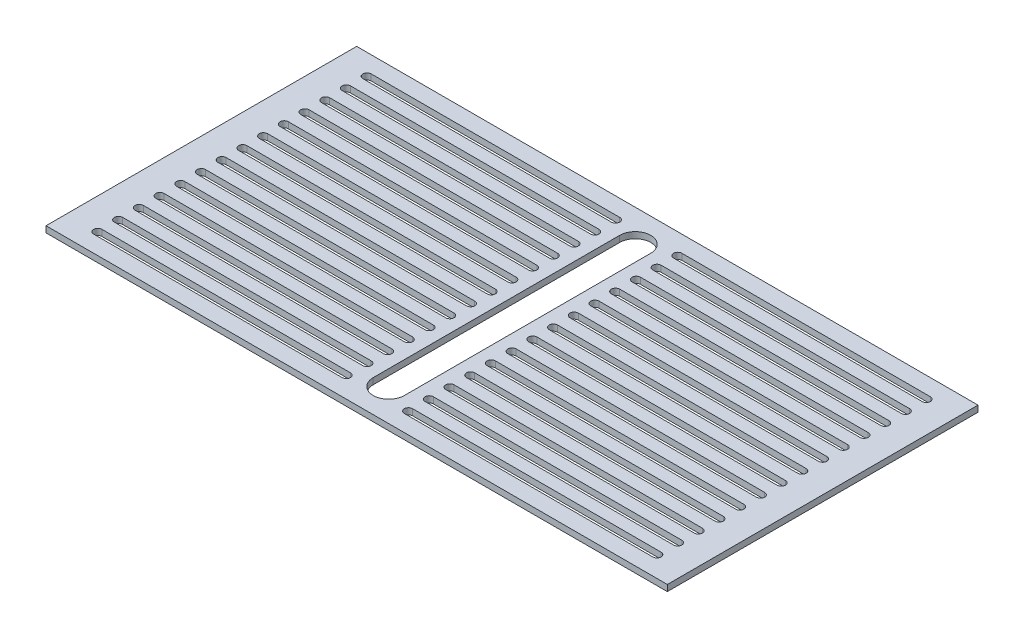
SolidWorks part; units mm, degrees
ref_plane "Front Plane" through (0, 0, 0) normal (0, 0, 1) x (1, 0, 0)
ref_plane "Top Plane" through (0, 0, 0) normal (0, 1, 0) x (1, 0, 0)
ref_plane "Right Plane" through (0, 0, 0) normal (1, 0, 0) x (0, 0, -1)
sketch "Sketch1" plane through (0, 0, 0) normal (0, 1, 0) x (1, 0, 0)
  line L1 (-150, 75) -> (150, 75)
  line L2 (-150, 75) -> (-150, -75)
  line L3 (-150, -75) -> (150, -75)
  line L4 (150, 75) -> (150, -75)
  line L5 (-150, 75) -> (150, -75) construction
  line L6 (-150, -75) -> (150, 75) construction
  point P0 (0, 0)
  dimension "D1" = 300
  dimension "D2" = 150
extrude "Boss-Extrude1" add sketch "Sketch1" along normal blind 3
sketch "Sketch2" plane through (0, 3, 0) normal (0, 1, 0) x (1, 0, 0)
  line L0 (0, 75) -> (0, -75) construction
  line L1 (150, 75) -> (-150, 75) construction
  line L2 (-150, -75) -> (150, -75) construction
  line L3 (-150, 0) -> (150, 0) construction
  line L4 (-150, 75) -> (-150, -75) construction
  line L5 (150, -75) -> (150, 75) construction
  line L6 (-150, 65) -> (0, 65) construction
  line L7 (-135, 65) -> (-15, 65) construction
  line L8 (-135, 67) -> (-15, 67)
  line L9 (-135, 63) -> (-15, 63)
  line L10 (15, 65) -> (135, 65) construction
  line L11 (15, 67) -> (135, 67)
  line L12 (15, 63) -> (135, 63)
  line L13 (15, 55) -> (135, 55) construction
  line L14 (15, 57) -> (135, 57)
  line L15 (15, 53) -> (135, 53)
  line L16 (15, 45) -> (135, 45) construction
  line L17 (15, 47) -> (135, 47)
  line L18 (15, 43) -> (135, 43)
  line L19 (15, 35) -> (135, 35) construction
  line L20 (15, 37) -> (135, 37)
  line L21 (15, 33) -> (135, 33)
  line L22 (15, 25) -> (135, 25) construction
  line L23 (15, 27) -> (135, 27)
  line L24 (15, 23) -> (135, 23)
  line L25 (15, 15) -> (135, 15) construction
  line L26 (15, 17) -> (135, 17)
  line L27 (15, 13) -> (135, 13)
  line L28 (15, 5) -> (135, 5) construction
  line L29 (15, 7) -> (135, 7)
  line L30 (15, 3) -> (135, 3)
  line L31 (15, -5) -> (135, -5) construction
  line L32 (15, -3) -> (135, -3)
  line L33 (15, -7) -> (135, -7)
  line L34 (15, -15) -> (135, -15) construction
  line L35 (15, -13) -> (135, -13)
  line L36 (15, -17) -> (135, -17)
  line L37 (15, -25) -> (135, -25) construction
  line L38 (15, -23) -> (135, -23)
  line L39 (15, -27) -> (135, -27)
  line L40 (15, -35) -> (135, -35) construction
  line L41 (15, -33) -> (135, -33)
  line L42 (15, -37) -> (135, -37)
  line L43 (15, -45) -> (135, -45) construction
  line L44 (15, -43) -> (135, -43)
  line L45 (15, -47) -> (135, -47)
  line L46 (15, -55) -> (135, -55) construction
  line L47 (15, -53) -> (135, -53)
  line L48 (15, -57) -> (135, -57)
  line L49 (15, -65) -> (135, -65) construction
  line L50 (15, -63) -> (135, -63)
  line L51 (15, -67) -> (135, -67)
  line L52 (-135, 55) -> (-15, 55) construction
  line L53 (-135, 57) -> (-15, 57)
  line L54 (-135, 53) -> (-15, 53)
  line L55 (-135, 45) -> (-15, 45) construction
  line L56 (-135, 47) -> (-15, 47)
  line L57 (-135, 43) -> (-15, 43)
  line L58 (-135, 35) -> (-15, 35) construction
  line L59 (-135, 37) -> (-15, 37)
  line L60 (-135, 33) -> (-15, 33)
  line L61 (-135, 25) -> (-15, 25) construction
  line L62 (-135, 27) -> (-15, 27)
  line L63 (-135, 23) -> (-15, 23)
  line L64 (-135, 15) -> (-15, 15) construction
  line L65 (-135, 17) -> (-15, 17)
  line L66 (-135, 13) -> (-15, 13)
  line L67 (-135, 5) -> (-15, 5) construction
  line L68 (-135, 7) -> (-15, 7)
  line L69 (-135, 3) -> (-15, 3)
  line L70 (-135, -5) -> (-15, -5) construction
  line L71 (-135, -3) -> (-15, -3)
  line L72 (-135, -7) -> (-15, -7)
  line L73 (-135, -15) -> (-15, -15) construction
  line L74 (-135, -13) -> (-15, -13)
  line L75 (-135, -17) -> (-15, -17)
  line L76 (-135, -25) -> (-15, -25) construction
  line L77 (-135, -23) -> (-15, -23)
  line L78 (-135, -27) -> (-15, -27)
  line L79 (-135, -35) -> (-15, -35) construction
  line L80 (-135, -33) -> (-15, -33)
  line L81 (-135, -37) -> (-15, -37)
  line L82 (-135, -45) -> (-15, -45) construction
  line L83 (-135, -43) -> (-15, -43)
  line L84 (-135, -47) -> (-15, -47)
  line L85 (-135, -55) -> (-15, -55) construction
  line L86 (-135, -53) -> (-15, -53)
  line L87 (-135, -57) -> (-15, -57)
  line L88 (-135, -65) -> (-15, -65) construction
  line L89 (-135, -63) -> (-15, -63)
  line L90 (-135, -67) -> (-15, -67)
  line L91 (-75, 65) -> (-75, 55) construction
  line L92 (-135, 65) -> (-135, 75) construction
  line L93 (0, -59.5) -> (0, 59.5) construction
  line L94 (-7.5, -59.5) -> (-7.5, 59.5)
  line L95 (7.5, -59.5) -> (7.5, 59.5)
  line L96 (0, 67) -> (-15, 67) construction
  arc A0 (-135, 67) -> (-135, 63) centre (-135, 65) ccw
  arc A1 (-15, 63) -> (-15, 67) centre (-15, 65) ccw
  arc A2 (15, 67) -> (15, 63) centre (15, 65) ccw
  arc A3 (135, 63) -> (135, 67) centre (135, 65) ccw
  arc A4 (15, 57) -> (15, 53) centre (15, 55) ccw
  arc A5 (135, 53) -> (135, 57) centre (135, 55) ccw
  arc A6 (15, 47) -> (15, 43) centre (15, 45) ccw
  arc A7 (135, 43) -> (135, 47) centre (135, 45) ccw
  arc A8 (15, 37) -> (15, 33) centre (15, 35) ccw
  arc A9 (135, 33) -> (135, 37) centre (135, 35) ccw
  arc A10 (15, 27) -> (15, 23) centre (15, 25) ccw
  arc A11 (135, 23) -> (135, 27) centre (135, 25) ccw
  arc A12 (15, 17) -> (15, 13) centre (15, 15) ccw
  arc A13 (135, 13) -> (135, 17) centre (135, 15) ccw
  arc A14 (15, 7) -> (15, 3) centre (15, 5) ccw
  arc A15 (135, 3) -> (135, 7) centre (135, 5) ccw
  arc A16 (15, -3) -> (15, -7) centre (15, -5) ccw
  arc A17 (135, -7) -> (135, -3) centre (135, -5) ccw
  arc A18 (15, -13) -> (15, -17) centre (15, -15) ccw
  arc A19 (135, -17) -> (135, -13) centre (135, -15) ccw
  arc A20 (15, -23) -> (15, -27) centre (15, -25) ccw
  arc A21 (135, -27) -> (135, -23) centre (135, -25) ccw
  arc A22 (15, -33) -> (15, -37) centre (15, -35) ccw
  arc A23 (135, -37) -> (135, -33) centre (135, -35) ccw
  arc A24 (15, -43) -> (15, -47) centre (15, -45) ccw
  arc A25 (135, -47) -> (135, -43) centre (135, -45) ccw
  arc A26 (15, -53) -> (15, -57) centre (15, -55) ccw
  arc A27 (135, -57) -> (135, -53) centre (135, -55) ccw
  arc A28 (15, -63) -> (15, -67) centre (15, -65) ccw
  arc A29 (135, -67) -> (135, -63) centre (135, -65) ccw
  arc A30 (-135, 57) -> (-135, 53) centre (-135, 55) ccw
  arc A31 (-15, 53) -> (-15, 57) centre (-15, 55) ccw
  arc A32 (-135, 47) -> (-135, 43) centre (-135, 45) ccw
  arc A33 (-15, 43) -> (-15, 47) centre (-15, 45) ccw
  arc A34 (-135, 37) -> (-135, 33) centre (-135, 35) ccw
  arc A35 (-15, 33) -> (-15, 37) centre (-15, 35) ccw
  arc A36 (-135, 27) -> (-135, 23) centre (-135, 25) ccw
  arc A37 (-15, 23) -> (-15, 27) centre (-15, 25) ccw
  arc A38 (-135, 17) -> (-135, 13) centre (-135, 15) ccw
  arc A39 (-15, 13) -> (-15, 17) centre (-15, 15) ccw
  arc A40 (-135, 7) -> (-135, 3) centre (-135, 5) ccw
  arc A41 (-15, 3) -> (-15, 7) centre (-15, 5) ccw
  arc A42 (-135, -3) -> (-135, -7) centre (-135, -5) ccw
  arc A43 (-15, -7) -> (-15, -3) centre (-15, -5) ccw
  arc A44 (-135, -13) -> (-135, -17) centre (-135, -15) ccw
  arc A45 (-15, -17) -> (-15, -13) centre (-15, -15) ccw
  arc A46 (-135, -23) -> (-135, -27) centre (-135, -25) ccw
  arc A47 (-15, -27) -> (-15, -23) centre (-15, -25) ccw
  arc A48 (-135, -33) -> (-135, -37) centre (-135, -35) ccw
  arc A49 (-15, -37) -> (-15, -33) centre (-15, -35) ccw
  arc A50 (-135, -43) -> (-135, -47) centre (-135, -45) ccw
  arc A51 (-15, -47) -> (-15, -43) centre (-15, -45) ccw
  arc A52 (-135, -53) -> (-135, -57) centre (-135, -55) ccw
  arc A53 (-15, -57) -> (-15, -53) centre (-15, -55) ccw
  arc A54 (-135, -63) -> (-135, -67) centre (-135, -65) ccw
  arc A55 (-15, -67) -> (-15, -63) centre (-15, -65) ccw
  arc A56 (-7.5, -59.5) -> (7.5, -59.5) centre (0, -59.5) ccw
  arc A57 (7.5, 59.5) -> (-7.5, 59.5) centre (0, 59.5) ccw
  point P16 (-75, 65)
  point P26 (75, 65)
  point P33 (75, 55)
  point P40 (75, 45)
  point P47 (75, 35)
  point P54 (75, 25)
  point P61 (75, 15)
  point P68 (75, 5)
  point P75 (75, -5)
  point P82 (75, -15)
  point P89 (75, -25)
  point P96 (75, -35)
  point P103 (75, -45)
  point P110 (75, -55)
  point P117 (75, -65)
  point P124 (-75, 55)
  point P131 (-75, 45)
  point P138 (-75, 35)
  point P145 (-75, 25)
  point P152 (-75, 15)
  point P159 (-75, 5)
  point P166 (-75, -5)
  point P173 (-75, -15)
  point P180 (-75, -25)
  point P187 (-75, -35)
  point P194 (-75, -45)
  point P201 (-75, -55)
  point P208 (-75, -65)
  point P215 (0, 0)
  dimension "D1" = 10
  dimension "D2" = 4
  dimension "D3" = 120
  dimension "D6" = 15
  dimension "D4" = 2
  dimension "D5" = 14
extrude "Cut-Extrude1" cut sketch "Sketch2" against normal up to next (3 mm away)
